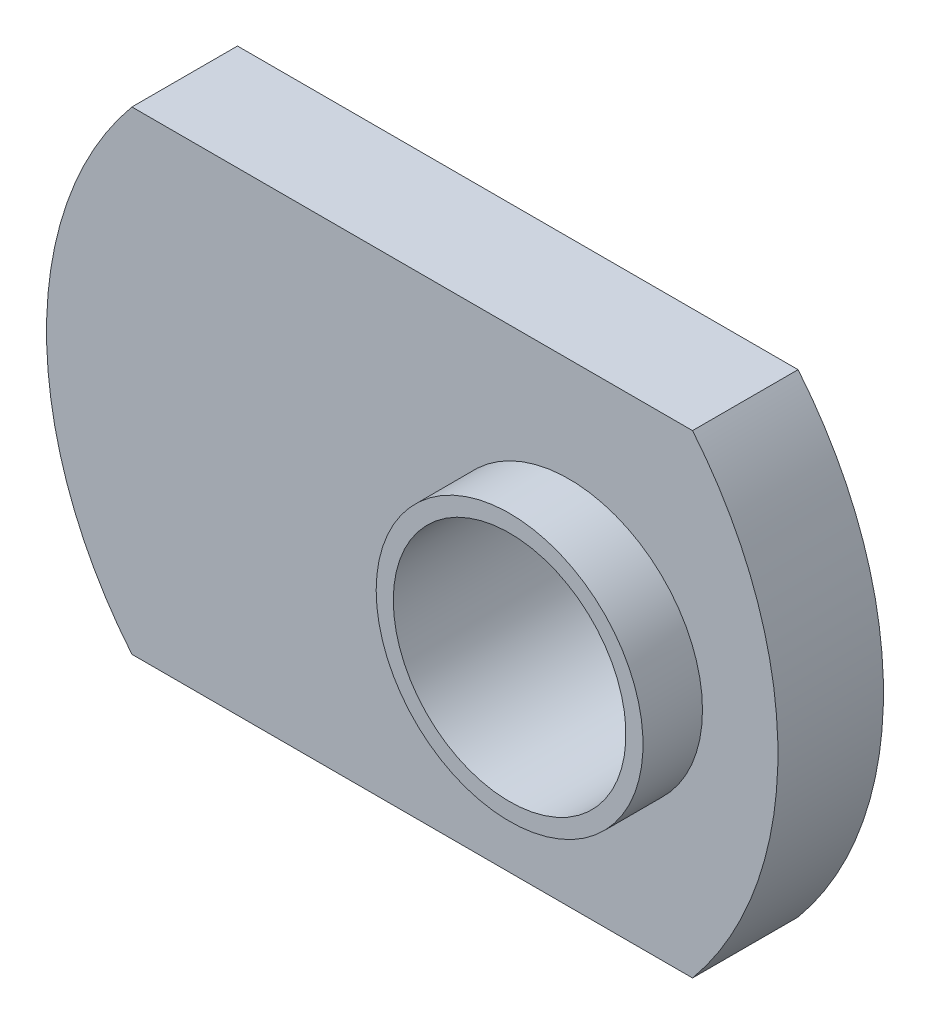
SolidWorks part; units mm, degrees
ref_plane "Front Plane" through (0, 0, 0) normal (0, 0, 1) x (1, 0, 0)
ref_plane "Top Plane" through (0, 0, 0) normal (0, 1, 0) x (1, 0, 0)
ref_plane "Right Plane" through (0, 0, 0) normal (1, 0, 0) x (0, 0, -1)
ref_plane "Plane1" through (0, 0, 3.6068) normal (0, 0, 1) x (1, 0, 0)
sketch "Sketch1" plane through (0, 0, 3.6068) normal (0, 0, 1) x (1, 0, 0)
  line L0 (102.3414, 120.3713) -> (121.4981, 120.3713)
  line L1 (121.4981, 136.5714) -> (102.3414, 136.5714)
  arc A0 (102.3414, 136.5714) -> (102.3414, 120.3713) centre (112.123, 128.4713) ccw
  arc A1 (121.4981, 120.3713) -> (121.4981, 136.5714) centre (111.7166, 128.4713) ccw
extrude "Boss-Extrude1" add sketch "Sketch1" against normal blind 3.6068
ref_plane "Plane2" through (0, 128.4713, 0) normal (0, -1, 0) x (1, 0, 0)
sketch "Sketch2" plane through (0, 128.4713, 0) normal (0, -1, 0) x (1, 0, 0)
  line L0 (121.8385, 5.6388) -> (117.2792, 5.6388)
  line L1 (117.2792, 5.6388) -> (117.2792, 3.6068)
  line L2 (117.2792, 3.6068) -> (121.8385, 3.6068)
  line L3 (121.8385, 3.6068) -> (121.8385, 5.6388)
  line L4 (117.2792, 5.6388) -> (117.2792, 3.6068) construction
revolve "Revolve1" add sketch "Sketch2" angle 360 about L4
hole_wizard "M7 Clearance Hole1" positions "Sketch4" profile "Sketch3" hole size "M7" standard "Ansi Metric"
sketch "Sketch4" plane through (0, 0, 0) normal (0, 0, -1) x (-1, 0, 0)
  point P0 (-117.2792, 128.4713)
sketch "Sketch3" plane through (117.2792, 128.4713, 0) normal (1, 0, 0) x (0, 1, 0)
  line L0 (0, 0) -> (0, 5.6388)
  line L1 (0, 5.6388) -> (3.9751, 5.6388)
  line L2 (3.9751, 5.6388) -> (3.9751, 0)
  line L5 (3.9751, 0) -> (0, 0)
  line L11 (0, -6.35) -> (0, 107.95) construction
  dimension "Thru Hole Dia." = 7.9502
  dimension "Thru Hole Depth" = 5.6388
